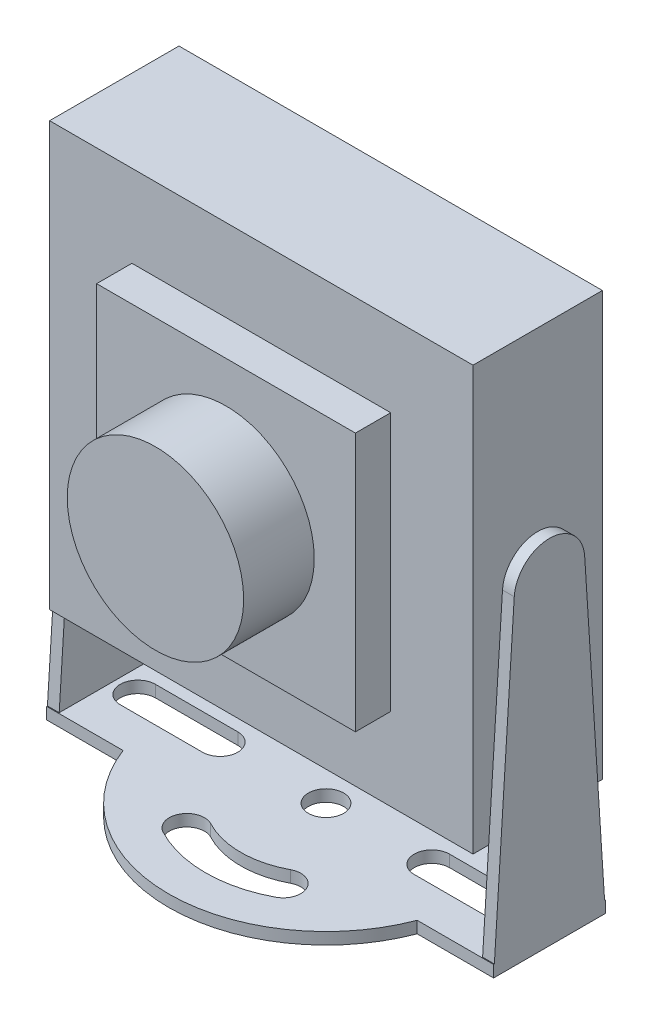
SolidWorks part; units mm, degrees
ref_plane "前视基准面" through (0, 0, 0) normal (0, 0, 1) x (1, 0, 0)
ref_plane "上视基准面" through (0, 0, 0) normal (0, 1, 0) x (1, 0, 0)
ref_plane "右视基准面" through (0, 0, 0) normal (1, 0, 0) x (0, 0, -1)
other "Configuration Table"
sketch "草图1" plane through (0, 0, 0) normal (0, 0, 1) x (1, 0, 0)
  line L1 (-18, 18) -> (18, 18)
  line L2 (-18, 18) -> (-18, -18)
  line L3 (-18, -18) -> (18, -18)
  line L4 (18, 18) -> (18, -18)
  line L5 (-18, 18) -> (18, -18) construction
  line L6 (-18, -18) -> (18, 18) construction
  point P0 (0, 0)
  dimension "D1" = 36
  dimension "D2" = 36
extrude "凸台-拉伸1" add sketch "草图1" along normal blind 11
sketch "草图2" plane through (0, 0, 11) normal (0, 0, 1) x (1, 0, 0)
  line L1 (-11, 11) -> (11, 11)
  line L2 (-11, 11) -> (-11, -11)
  line L3 (-11, -11) -> (11, -11)
  line L4 (11, 11) -> (11, -11)
  line L5 (-11, 11) -> (11, -11) construction
  line L6 (-11, -11) -> (11, 11) construction
  point P0 (0, 0)
  dimension "D1" = 22
  dimension "D2" = 22
extrude "凸台-拉伸2" add sketch "草图2" along normal blind 3
sketch "草图3" plane through (0, 0, 14) normal (0, 0, 1) x (1, 0, 0)
  circle A0 centre (0, 0) radius 7.5
  dimension "D1" = 15
extrude "凸台-拉伸3" add sketch "草图3" along normal blind 6
sketch "草图4" plane through (18, 0, 0) normal (1, 0, 0) x (0, 0, -1)
  line L0 (-8.4938, 0.1933) -> (-10.25, -27)
  line L1 (-10.25, -27) -> (-0.75, -27)
  line L2 (-5.5, 18) -> (-5.5, -37.0091) construction
  line L3 (-11, 18) -> (0, 18) construction
  line L4 (-2.5062, 0.1933) -> (-0.75, -27)
  arc A0 (-2.5062, 0.1933) -> (-8.4938, 0.1933) centre (-5.5, 0) ccw
  dimension "D1" = 3
  dimension "D2" = 9.5
  dimension "D3" = 45
extrude "凸台-拉伸4" add sketch "草图4" along normal blind 1
mirror "镜向1" about plane through (0, 0, 0) normal (1, 0, 0) of "凸台-拉伸4"
sketch "草图5" plane through (0, -27, 0) normal (0, -1, 0) x (1, 0, 0)
  line L0 (-19, 5.5) -> (25.1038, 5.5) construction
  line L1 (-19, 10.25) -> (-12.5, 10.25)
  line L2 (-19, 10.25) -> (-19, 0.75)
  line L3 (-19, 0.75) -> (-12.5, 0.75)
  line L4 (19, 10.25) -> (19, 0.75)
  line L5 (12.5, 10.25) -> (19, 10.25)
  line L6 (12.5, 0.75) -> (19, 0.75)
  arc A0 (-12.5, 0.75) -> (12.5, 0.75) centre (0, 5.5) ccw
  arc A1 (12.5, 10.25) -> (-12.5, 10.25) centre (0, 5.5) ccw
  point P8 (12.5, 10.25)
  point P12 (-12.5, 10.25)
  dimension "D1" = 25
extrude "凸台-拉伸5" add sketch "草图5" against normal blind 1
sketch "草图6" plane through (0, -27, 0) normal (0, -1, 0) x (1, 0, 0)
  line L0 (-16, 5.5) -> (-9, 5.5) construction
  line L1 (-16, 7) -> (-9, 7)
  line L2 (-16, 4) -> (-9, 4)
  line L3 (0, 0) -> (0, 12.7501) construction
  line L4 (9, 5.5) -> (16, 5.5) construction
  line L5 (9, 7) -> (16, 7)
  line L6 (9, 4) -> (16, 4)
  line L7 (0, 15.7501) -> (0, 25.5273) construction
  line L8 (0, 5.5) -> (23.3442, 5.5) construction
  circle A0 centre (0, 5.5) radius 1.5
  arc A1 (-16, 7) -> (-16, 4) centre (-16, 5.5) ccw
  arc A2 (-9, 4) -> (-9, 7) centre (-9, 5.5) ccw
  arc A3 (12.5, 10.25) -> (-12.5, 10.25) centre (0, 5.5) ccw construction
  arc A4 (9, 7) -> (9, 4) centre (9, 5.5) ccw
  arc A5 (16, 4) -> (16, 7) centre (16, 5.5) ccw
  arc A6 (-4.7953, 14.5593) -> (4.7953, 14.5593) centre (0, 5.5) cw
  arc A7 (-3.3918, 11.9078) -> (3.3918, 11.9078) centre (0, 5.5) cw
  arc A8 (-4.7953, 14.5593) -> (-3.3918, 11.9078) centre (-4.0936, 13.2335) ccw
  arc A9 (4.7953, 14.5593) -> (3.3918, 11.9078) centre (4.0936, 13.2335) cw
  arc A10 (-4.7953, -3.5593) -> (-3.3918, -0.9078) centre (-4.0936, -2.2335) cw
  arc A11 (-4.7953, -3.5593) -> (4.7953, -3.5593) centre (0, 5.5) ccw
  arc A12 (-3.3918, -0.9078) -> (3.3918, -0.9078) centre (0, 5.5) ccw
  arc A13 (4.7953, -3.5593) -> (3.3918, -0.9078) centre (4.0936, -2.2335) ccw
  point P4 (-12.5, 5.5)
  point P9 (-7.5, 5.5)
  point P10 (-17.5, 5.5)
  point P19 (12.5, 5.5)
  dimension "D1" = 3
  dimension "D3" = 1.5
  dimension "D4" = 1.5
  dimension "D2" = 10
  dimension "D5" = 25
extrude "切除-拉伸1" cut sketch "草图6" against normal blind 1
